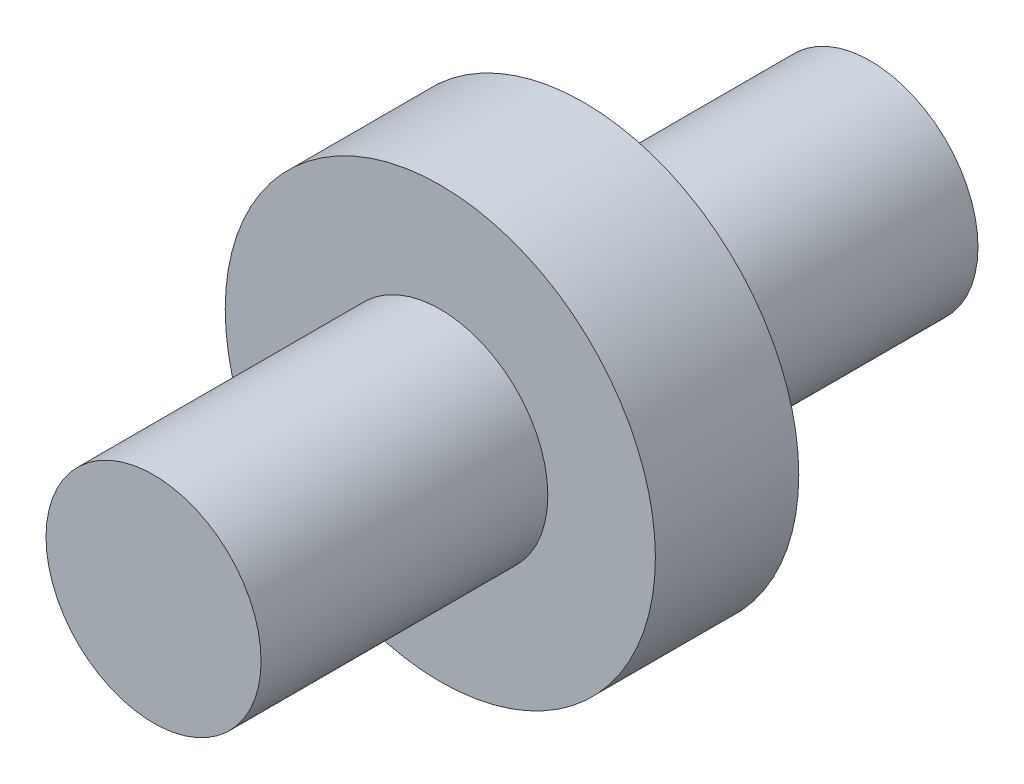
SolidWorks part; units mm, degrees
ref_plane "Front Plane" through (0, 0, 0) normal (0, 0, 1) x (1, 0, 0)
ref_plane "Top Plane" through (0, 0, 0) normal (0, 1, 0) x (1, 0, 0)
ref_plane "Right Plane" through (0, 0, 0) normal (1, 0, 0) x (0, 0, -1)
sketch "Sketch1" plane through (0, 0, 0) normal (0, 0, 1) x (1, 0, 0)
  circle A0 centre (0, 0) radius 9.525
  dimension "D1" = 19.05
extrude "Boss-Extrude1" add sketch "Sketch1" along normal blind 25.4
sketch "Sketch3" plane through (0, 0, 25.4) normal (0, 0, 1) x (1, 0, 0)
  circle A0 centre (0, 0) radius 19.05
  dimension "D1" = 38.1
extrude "Boss-Extrude3" add sketch "Sketch3" along normal blind 12.7
sketch "Sketch4" plane through (0, 0, 38.1) normal (0, 0, 1) x (1, 0, 0)
  circle A0 centre (0, 0) radius 9.525
  dimension "D1" = 19.05
extrude "Boss-Extrude4" add sketch "Sketch4" along normal blind 25.4
